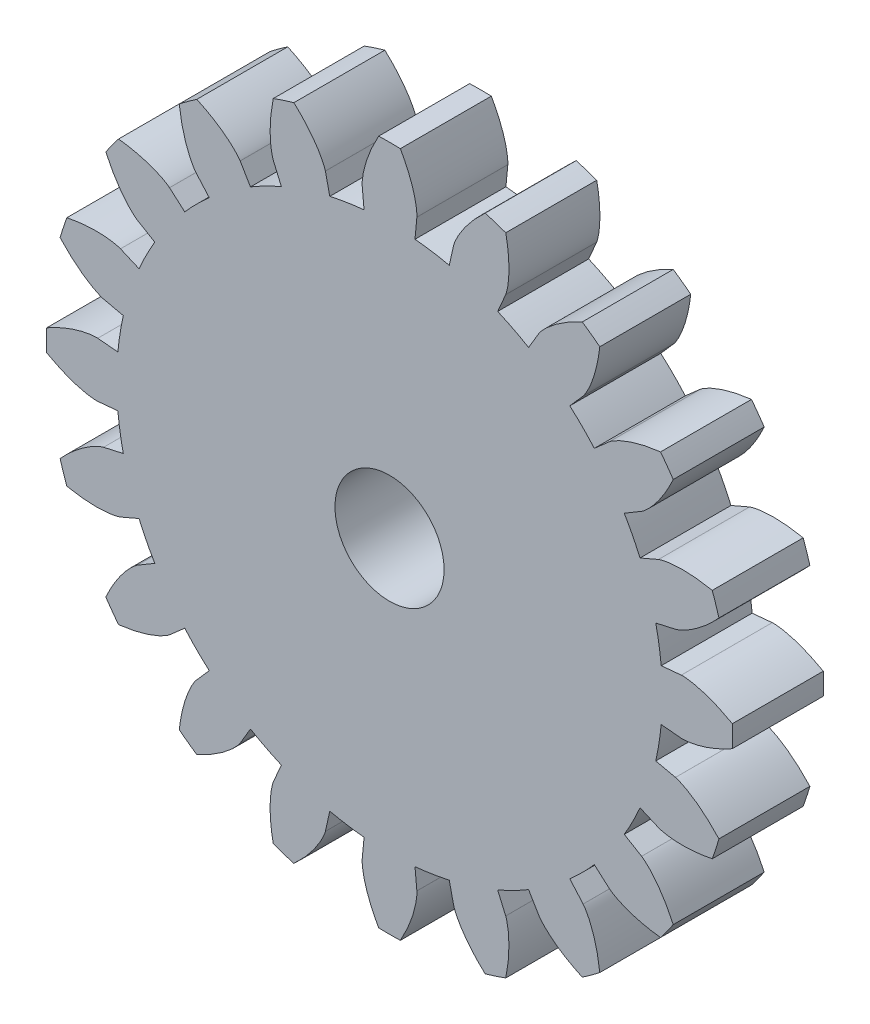
SolidWorks part; units mm, degrees
ref_plane "Plan de face" through (0, 0, 0) normal (0, 0, 1) x (1, 0, 0)
ref_plane "Plan de dessus" through (0, 0, 0) normal (0, 1, 0) x (1, 0, 0)
ref_plane "Plan de droite" through (0, 0, 0) normal (1, 0, 0) x (0, 0, -1)
sketch "Esquisse1" plane through (0, 0, 0) normal (0, 0, 1) x (1, 0, 0)
  line L0 (15.0618, -1.9866) -> (16.166, -2.0901)
  line L1 (16.166, -2.0901) -> (16.1672, -2.0902)
  line L2 (16.1672, 0.9162) -> (16.166, 0.9161)
  line L3 (16.166, 0.9161) -> (15.0618, 0.8126)
  line L4 (14.7634, 2.6969) -> (15.8455, 2.9397)
  line L5 (15.8455, 2.9397) -> (15.8467, 2.94)
  line L6 (14.9177, 5.7993) -> (14.9165, 5.7988)
  line L7 (14.9165, 5.7988) -> (13.8984, 5.3592)
  line L8 (13.0323, 7.059) -> (13.9864, 7.6243)
  line L9 (13.9864, 7.6243) -> (13.9875, 7.625)
  line L10 (12.2203, 10.0572) -> (12.2194, 10.0564)
  line L11 (12.2194, 10.0564) -> (11.3869, 9.3237)
  line L12 (10.0379, 10.6727) -> (10.7706, 11.5051)
  line L13 (10.7706, 11.5051) -> (10.7715, 11.5061)
  line L14 (8.3392, 13.2732) -> (8.3386, 13.2721)
  line L15 (8.3386, 13.2721) -> (7.7733, 12.318)
  line L16 (6.0734, 13.1841) -> (6.5131, 14.2023)
  line L17 (6.5131, 14.2023) -> (6.5135, 14.2034)
  line L18 (3.6543, 15.1325) -> (3.654, 15.1313)
  line L19 (3.654, 15.1313) -> (3.4112, 14.0491)
  line L20 (1.5269, 14.3476) -> (1.6304, 15.4518)
  line L21 (1.6304, 15.4518) -> (1.6305, 15.453)
  line L22 (-1.3759, 15.453) -> (-1.3758, 15.4518)
  line L23 (-1.3758, 15.4518) -> (-1.2724, 14.3476)
  line L24 (-3.1566, 14.0491) -> (-3.3994, 15.1313)
  line L25 (-3.3994, 15.1313) -> (-3.3997, 15.1325)
  line L26 (-6.259, 14.2034) -> (-6.2585, 14.2023)
  line L27 (-6.2585, 14.2023) -> (-5.8189, 13.1841)
  line L28 (-7.5187, 12.318) -> (-8.084, 13.2721)
  line L29 (-8.084, 13.2721) -> (-8.0847, 13.2732)
  line L30 (-10.5169, 11.5061) -> (-10.5161, 11.5051)
  line L31 (-10.5161, 11.5051) -> (-9.7834, 10.6727)
  line L32 (-11.1324, 9.3237) -> (-11.9648, 10.0564)
  line L33 (-11.9648, 10.0564) -> (-11.9658, 10.0572)
  line L34 (-13.7329, 7.625) -> (-13.7318, 7.6243)
  line L35 (-13.7318, 7.6243) -> (-12.7777, 7.059)
  line L36 (-13.6438, 5.3592) -> (-14.662, 5.7988)
  line L37 (-14.662, 5.7988) -> (-14.6631, 5.7993)
  line L38 (-15.5922, 2.94) -> (-15.591, 2.9397)
  line L39 (-15.591, 2.9397) -> (-14.5088, 2.6969)
  line L40 (-14.8073, 0.8126) -> (-15.9115, 0.9161)
  line L41 (-15.9115, 0.9161) -> (-15.9127, 0.9162)
  line L42 (-15.9127, -2.0902) -> (-15.9115, -2.0901)
  line L43 (-15.9115, -2.0901) -> (-14.8073, -1.9866)
  line L44 (-14.5088, -3.8709) -> (-15.591, -4.1137)
  line L45 (-15.591, -4.1137) -> (-15.5922, -4.114)
  line L46 (-14.6631, -6.9732) -> (-14.662, -6.9728)
  line L47 (-14.662, -6.9728) -> (-13.6438, -6.5331)
  line L48 (-12.7777, -8.233) -> (-13.7318, -8.7983)
  line L49 (-13.7318, -8.7983) -> (-13.7329, -8.7989)
  line L50 (-11.9658, -11.2312) -> (-11.9648, -11.2303)
  line L51 (-11.9648, -11.2303) -> (-11.1324, -10.4976)
  line L52 (-9.7834, -11.8466) -> (-10.5161, -12.6791)
  line L53 (-10.5161, -12.6791) -> (-10.5169, -12.68)
  line L54 (-8.0847, -14.4472) -> (-8.084, -14.4461)
  line L55 (-8.084, -14.4461) -> (-7.5187, -13.492)
  line L56 (-5.8189, -14.3581) -> (-6.2585, -15.3762)
  line L57 (-6.2585, -15.3762) -> (-6.259, -15.3774)
  line L58 (-3.3997, -16.3064) -> (-3.3994, -16.3052)
  line L59 (-3.3994, -16.3052) -> (-3.1566, -15.2231)
  line L60 (-1.2724, -15.5215) -> (-1.3758, -16.6257)
  line L61 (-1.3758, -16.6257) -> (-1.3759, -16.6269)
  line L62 (1.6305, -16.6269) -> (1.6304, -16.6257)
  line L63 (1.6304, -16.6257) -> (1.5269, -15.5215)
  line L64 (3.4112, -15.2231) -> (3.654, -16.3052)
  line L65 (3.654, -16.3052) -> (3.6543, -16.3064)
  line L66 (6.5135, -15.3774) -> (6.5131, -15.3762)
  line L67 (6.5131, -15.3762) -> (6.0734, -14.3581)
  line L68 (7.7733, -13.492) -> (8.3386, -14.4461)
  line L69 (8.3386, -14.4461) -> (8.3392, -14.4472)
  line L70 (10.7715, -12.68) -> (10.7706, -12.6791)
  line L71 (10.7706, -12.6791) -> (10.0379, -11.8466)
  line L72 (11.3869, -10.4976) -> (12.2194, -11.2303)
  line L73 (12.2194, -11.2303) -> (12.2203, -11.2312)
  line L74 (13.9875, -8.7989) -> (13.9864, -8.7983)
  line L75 (13.9864, -8.7983) -> (13.0323, -8.233)
  line L76 (13.8984, -6.5331) -> (14.9165, -6.9728)
  line L77 (14.9165, -6.9728) -> (14.9177, -6.9732)
  line L78 (15.8467, -4.114) -> (15.8455, -4.1137)
  line L79 (15.8455, -4.1137) -> (14.7634, -3.8709)
  arc A0 (14.7634, -3.8709) -> (15.0618, -1.9866) centre (0.1273, -0.587) ccw
  arc A1 (18.975, -1.1825) -> (18.975, 0.0085) centre (0.1273, -0.587) ccw
  arc A2 (15.0618, 0.8126) -> (14.7634, 2.6969) centre (0.1273, -0.587) ccw
  arc A3 (18.2366, 4.6709) -> (17.8685, 5.8037) centre (0.1273, -0.587) ccw
  arc A4 (13.8984, 5.3592) -> (13.0323, 7.059) centre (0.1273, -0.587) ccw
  arc A5 (15.7254, 10.0097) -> (15.0254, 10.9732) centre (0.1273, -0.587) ccw
  arc A6 (11.3869, 9.3237) -> (10.0379, 10.6727) centre (0.1273, -0.587) ccw
  arc A7 (11.6875, 14.3111) -> (10.7239, 15.0112) centre (0.1273, -0.587) ccw
  arc A8 (7.7733, 12.318) -> (6.0734, 13.1841) centre (0.1273, -0.587) ccw
  arc A9 (6.5179, 17.1543) -> (5.3852, 17.5223) centre (0.1273, -0.587) ccw
  arc A10 (3.4112, 14.0491) -> (1.5269, 14.3476) centre (0.1273, -0.587) ccw
  arc A11 (0.7228, 18.2608) -> (-0.4682, 18.2608) centre (0.1273, -0.587) ccw
  arc A12 (-1.2724, 14.3476) -> (-3.1566, 14.0491) centre (0.1273, -0.587) ccw
  arc A13 (-5.1306, 17.5223) -> (-6.2634, 17.1543) centre (0.1273, -0.587) ccw
  arc A14 (-5.8189, 13.1841) -> (-7.5187, 12.318) centre (0.1273, -0.587) ccw
  arc A15 (-10.4694, 15.0112) -> (-11.4329, 14.3111) centre (0.1273, -0.587) ccw
  arc A16 (-9.7834, 10.6727) -> (-11.1324, 9.3237) centre (0.1273, -0.587) ccw
  arc A17 (-14.7708, 10.9732) -> (-15.4709, 10.0097) centre (0.1273, -0.587) ccw
  arc A18 (-12.7777, 7.059) -> (-13.6438, 5.3592) centre (0.1273, -0.587) ccw
  arc A19 (-17.614, 5.8037) -> (-17.982, 4.6709) centre (0.1273, -0.587) ccw
  arc A20 (-14.5088, 2.6969) -> (-14.8073, 0.8126) centre (0.1273, -0.587) ccw
  arc A21 (-18.7205, 0.0085) -> (-18.7205, -1.1825) centre (0.1273, -0.587) ccw
  arc A22 (-14.8073, -1.9866) -> (-14.5088, -3.8709) centre (0.1273, -0.587) ccw
  arc A23 (-17.982, -5.8449) -> (-17.614, -6.9776) centre (0.1273, -0.587) ccw
  arc A24 (-13.6438, -6.5331) -> (-12.7777, -8.233) centre (0.1273, -0.587) ccw
  arc A25 (-15.4709, -11.1836) -> (-14.7708, -12.1472) centre (0.1273, -0.587) ccw
  arc A26 (-11.1324, -10.4976) -> (-9.7834, -11.8466) centre (0.1273, -0.587) ccw
  arc A27 (-11.4329, -15.4851) -> (-10.4694, -16.1851) centre (0.1273, -0.587) ccw
  arc A28 (-7.5187, -13.492) -> (-5.8189, -14.3581) centre (0.1273, -0.587) ccw
  arc A29 (-6.2634, -18.3282) -> (-5.1306, -18.6963) centre (0.1273, -0.587) ccw
  arc A30 (-3.1566, -15.2231) -> (-1.2724, -15.5215) centre (0.1273, -0.587) ccw
  arc A31 (-0.4682, -19.4347) -> (0.7228, -19.4347) centre (0.1273, -0.587) ccw
  arc A32 (1.5269, -15.5215) -> (3.4112, -15.2231) centre (0.1273, -0.587) ccw
  arc A33 (5.3852, -18.6963) -> (6.5179, -18.3282) centre (0.1273, -0.587) ccw
  arc A34 (6.0734, -14.3581) -> (7.7733, -13.492) centre (0.1273, -0.587) ccw
  arc A35 (10.7239, -16.1851) -> (11.6875, -15.4851) centre (0.1273, -0.587) ccw
  arc A36 (10.0379, -11.8466) -> (11.3869, -10.4976) centre (0.1273, -0.587) ccw
  arc A37 (15.0254, -12.1472) -> (15.7254, -11.1836) centre (0.1273, -0.587) ccw
  arc A38 (13.0323, -8.233) -> (13.8984, -6.5331) centre (0.1273, -0.587) ccw
  arc A39 (17.8685, -6.9776) -> (18.2366, -5.8449) centre (0.1273, -0.587) ccw
  spline S0 degree 5 poles (16.1672, -2.0902) (16.168, -2.0902) (16.1695, -2.0904) (16.1722, -2.0906) (16.1781, -2.0909) (16.1878, -2.0914) (16.1996, -2.0918) (16.2161, -2.0922) (16.2383, -2.0924) (16.2646, -2.0921) (16.2978, -2.0913) (16.3386, -2.0896) (16.388, -2.0865) (16.4465, -2.0817) (16.515, -2.0746) (16.596, -2.0644) (16.6885, -2.0505) (16.7929, -2.0322) (16.9096, -2.0087) (17.0392, -1.9792) (17.1818, -1.9428) (17.3378, -1.8984) (17.5073, -1.8452) (17.6906, -1.7819) (17.8876, -1.7074) (18.1071, -1.6173) (18.3138, -1.5248) (18.5026, -1.434) (18.6721, -1.3477) (18.8059, -1.2764) (18.8809, -1.2353) (18.9342, -1.2055) (18.9656, -1.1878) (18.975, -1.1825) knots 0 0 0 0 0 0 0.016667 0.025 0.033333 0.054167 0.066667 0.083333 0.104167 0.125 0.15 0.175 0.204167 0.2375 0.270833 0.308333 0.35 0.391667 0.4375 0.483333 0.533333 0.5875 0.641667 0.7 0.758333 0.820833 0.9 0.929167 0.958333 0.9875 1 1 1 1 1 1 weights 1 1 1 1 1 1 1 1 1 1 1 1 1 1 1 1 1 1 1 1 1 1 1 1 1 1 1 1 1 1 1 1 1 1
  spline S1 degree 5 poles (18.975, 0.0085) (18.9153, 0.0423) (18.837, 0.0857) (18.7341, 0.1412) (18.5949, 0.2136) (18.4234, 0.298) (18.278, 0.3664) (18.1136, 0.4396) (17.9373, 0.5133) (17.7616, 0.5816) (17.5816, 0.6462) (17.3961, 0.707) (17.2119, 0.7612) (17.0307, 0.8081) (16.8333, 0.8519) (16.6491, 0.8844) (16.4939, 0.9045) (16.3642, 0.9152) (16.2755, 0.9184) (16.2285, 0.9185) (16.2015, 0.918) (16.1853, 0.9173) (16.1771, 0.9169) (16.1721, 0.9166) (16.1692, 0.9164) (16.1678, 0.9163) (16.1672, 0.9162) knots -1 -1 -1 -1 -1 -1 -0.920833 -0.895833 -0.8625 -0.8125 -0.766667 -0.720833 -0.666667 -0.6125 -0.558333 -0.5 -0.4375 -0.375 -0.3125 -0.2125 -0.15 -0.108333 -0.058333 -0.045833 -0.0375 -0.025 -0.0125 0 0 0 0 0 0 weights 1 1 1 1 1 1 1 1 1 1 1 1 1 1 1 1 1 1 1 1 1 1 1 1 1 1 1
  spline S2 degree 5 poles (15.8467, 2.94) (15.8475, 2.9402) (15.8489, 2.9405) (15.8516, 2.9412) (15.8573, 2.9427) (15.8666, 2.9452) (15.878, 2.9484) (15.8938, 2.9532) (15.915, 2.9599) (15.9399, 2.9682) (15.9712, 2.9793) (16.0095, 2.9936) (16.0555, 3.0117) (16.1097, 3.0344) (16.1727, 3.0623) (16.2466, 3.0971) (16.3302, 3.1388) (16.4238, 3.1885) (16.5276, 3.2469) (16.6417, 3.315) (16.766, 3.3937) (16.9007, 3.4841) (17.0455, 3.5871) (17.2002, 3.704) (17.3646, 3.8356) (17.5455, 3.9893) (17.7135, 4.1411) (17.865, 4.2857) (17.9996, 4.4202) (18.1047, 4.5294) (18.1634, 4.5916) (18.2049, 4.6364) (18.2292, 4.6629) (18.2366, 4.6709) knots 0 0 0 0 0 0 0.016667 0.025 0.033333 0.054167 0.066667 0.083333 0.104167 0.125 0.15 0.175 0.204167 0.2375 0.270833 0.308333 0.35 0.391667 0.4375 0.483333 0.533333 0.5875 0.641667 0.7 0.758333 0.820833 0.9 0.929167 0.958333 0.9875 1 1 1 1 1 1 weights 1 1 1 1 1 1 1 1 1 1 1 1 1 1 1 1 1 1 1 1 1 1 1 1 1 1 1 1 1 1 1 1 1 1
  spline S3 degree 5 poles (17.8685, 5.8037) (17.8013, 5.8174) (17.7134, 5.8344) (17.5984, 5.8554) (17.4436, 5.8812) (17.2545, 5.9085) (17.0951, 5.9286) (16.9161, 5.9475) (16.7256, 5.963) (16.5374, 5.9737) (16.3463, 5.9796) (16.151, 5.98) (15.9591, 5.9746) (15.7723, 5.9632) (15.571, 5.9439) (15.3858, 5.9179) (15.2319, 5.889) (15.1053, 5.8592) (15.02, 5.8348) (14.9752, 5.8204) (14.9497, 5.8115) (14.9345, 5.8059) (14.9269, 5.803) (14.9222, 5.8011) (14.9195, 5.8001) (14.9182, 5.7995) (14.9177, 5.7993) knots -1 -1 -1 -1 -1 -1 -0.920833 -0.895833 -0.8625 -0.8125 -0.766667 -0.720833 -0.666667 -0.6125 -0.558333 -0.5 -0.4375 -0.375 -0.3125 -0.2125 -0.15 -0.108333 -0.058333 -0.045833 -0.0375 -0.025 -0.0125 0 0 0 0 0 0 weights 1 1 1 1 1 1 1 1 1 1 1 1 1 1 1 1 1 1 1 1 1 1 1 1 1 1 1
  spline S4 degree 5 poles (13.9875, 7.625) (13.9881, 7.6254) (13.9894, 7.6261) (13.9917, 7.6276) (13.9967, 7.6307) (14.0048, 7.6361) (14.0146, 7.6426) (14.0281, 7.652) (14.0462, 7.665) (14.0673, 7.6806) (14.0937, 7.7008) (14.1257, 7.7262) (14.1639, 7.7577) (14.2084, 7.796) (14.2597, 7.842) (14.3192, 7.8979) (14.3858, 7.9635) (14.4595, 8.0396) (14.5402, 8.1272) (14.6276, 8.2272) (14.7216, 8.3405) (14.8217, 8.4681) (14.9276, 8.6109) (15.0386, 8.7698) (15.1543, 8.9458) (15.2789, 9.1478) (15.3917, 9.3441) (15.4911, 9.5285) (15.5775, 9.698) (15.6438, 9.8343) (15.6803, 9.9116) (15.706, 9.967) (15.721, 9.9998) (15.7254, 10.0097) knots 0 0 0 0 0 0 0.016667 0.025 0.033333 0.054167 0.066667 0.083333 0.104167 0.125 0.15 0.175 0.204167 0.2375 0.270833 0.308333 0.35 0.391667 0.4375 0.483333 0.533333 0.5875 0.641667 0.7 0.758333 0.820833 0.9 0.929167 0.958333 0.9875 1 1 1 1 1 1 weights 1 1 1 1 1 1 1 1 1 1 1 1 1 1 1 1 1 1 1 1 1 1 1 1 1 1 1 1 1 1 1 1 1 1
  spline S5 degree 5 poles (15.0254, 10.9732) (14.9572, 10.9655) (14.8684, 10.9546) (14.7525, 10.939) (14.5973, 10.9157) (14.409, 10.8832) (14.2512, 10.8531) (14.0751, 10.8157) (13.8892, 10.7716) (13.7069, 10.7236) (13.5233, 10.6701) (13.3374, 10.6102) (13.1566, 10.5458) (12.9824, 10.4772) (12.797, 10.3966) (12.6289, 10.3147) (12.4915, 10.2397) (12.3803, 10.1722) (12.3067, 10.1226) (12.2685, 10.0951) (12.247, 10.0787) (12.2343, 10.0687) (12.2279, 10.0636) (12.2241, 10.0604) (12.2218, 10.0585) (12.2208, 10.0576) (12.2203, 10.0572) knots -1 -1 -1 -1 -1 -1 -0.920833 -0.895833 -0.8625 -0.8125 -0.766667 -0.720833 -0.666667 -0.6125 -0.558333 -0.5 -0.4375 -0.375 -0.3125 -0.2125 -0.15 -0.108333 -0.058333 -0.045833 -0.0375 -0.025 -0.0125 0 0 0 0 0 0 weights 1 1 1 1 1 1 1 1 1 1 1 1 1 1 1 1 1 1 1 1 1 1 1 1 1 1 1
  spline S6 degree 5 poles (10.7715, 11.5061) (10.772, 11.5067) (10.7729, 11.5078) (10.7747, 11.5099) (10.7784, 11.5144) (10.7845, 11.522) (10.7918, 11.5313) (10.8018, 11.5444) (10.815, 11.5623) (10.8302, 11.5837) (10.8491, 11.611) (10.8717, 11.6451) (10.8982, 11.6868) (10.9288, 11.737) (10.9633, 11.7966) (11.0026, 11.8681) (11.0457, 11.9511) (11.0923, 12.0463) (11.1419, 12.1546) (11.1942, 12.2767) (11.2485, 12.4135) (11.3043, 12.5657) (11.3609, 12.7342) (11.4174, 12.9197) (11.473, 13.1229) (11.5291, 13.3534) (11.5757, 13.575) (11.6133, 13.7811) (11.6431, 13.969) (11.664, 14.1191) (11.6749, 14.204) (11.6821, 14.2645) (11.6863, 14.3004) (11.6875, 14.3111) knots 0 0 0 0 0 0 0.016667 0.025 0.033333 0.054167 0.066667 0.083333 0.104167 0.125 0.15 0.175 0.204167 0.2375 0.270833 0.308333 0.35 0.391667 0.4375 0.483333 0.533333 0.5875 0.641667 0.7 0.758333 0.820833 0.9 0.929167 0.958333 0.9875 1 1 1 1 1 1 weights 1 1 1 1 1 1 1 1 1 1 1 1 1 1 1 1 1 1 1 1 1 1 1 1 1 1 1 1 1 1 1 1 1 1
  spline S7 degree 5 poles (10.7239, 15.0112) (10.6615, 14.9828) (10.5804, 14.9449) (10.475, 14.8943) (10.3346, 14.8242) (10.1655, 14.7351) (10.0247, 14.6577) (9.8688, 14.5677) (9.7056, 14.4683) (9.5471, 14.3663) (9.389, 14.2588) (9.2308, 14.1443) (9.0787, 14.0272) (8.9342, 13.9082) (8.7828, 13.7742) (8.6482, 13.6443) (8.5407, 13.5305) (8.4558, 13.432) (8.4011, 13.3621) (8.3733, 13.3241) (8.3579, 13.3019) (8.3489, 13.2885) (8.3445, 13.2816) (8.3418, 13.2774) (8.3402, 13.2749) (8.3395, 13.2737) (8.3392, 13.2732) knots -1 -1 -1 -1 -1 -1 -0.920833 -0.895833 -0.8625 -0.8125 -0.766667 -0.720833 -0.666667 -0.6125 -0.558333 -0.5 -0.4375 -0.375 -0.3125 -0.2125 -0.15 -0.108333 -0.058333 -0.045833 -0.0375 -0.025 -0.0125 0 0 0 0 0 0 weights 1 1 1 1 1 1 1 1 1 1 1 1 1 1 1 1 1 1 1 1 1 1 1 1 1 1 1
  spline S8 degree 5 poles (6.5135, 14.2034) (6.5138, 14.2041) (6.5144, 14.2055) (6.5154, 14.208) (6.5176, 14.2135) (6.521, 14.2226) (6.5251, 14.2337) (6.5305, 14.2492) (6.5376, 14.2704) (6.5455, 14.2954) (6.5549, 14.3272) (6.5659, 14.3666) (6.5783, 14.4145) (6.5918, 14.4717) (6.6062, 14.539) (6.6215, 14.6192) (6.6369, 14.7115) (6.6517, 14.8163) (6.6655, 14.9347) (6.6774, 15.067) (6.6869, 15.2138) (6.6929, 15.3759) (6.6946, 15.5536) (6.691, 15.7475) (6.6812, 15.9579) (6.6632, 16.1945) (6.6391, 16.4196) (6.6112, 16.6272) (6.5814, 16.8152) (6.5549, 16.9644) (6.539, 17.0484) (6.5272, 17.1083) (6.5201, 17.1437) (6.5179, 17.1543) knots 0 0 0 0 0 0 0.016667 0.025 0.033333 0.054167 0.066667 0.083333 0.104167 0.125 0.15 0.175 0.204167 0.2375 0.270833 0.308333 0.35 0.391667 0.4375 0.483333 0.533333 0.5875 0.641667 0.7 0.758333 0.820833 0.9 0.929167 0.958333 0.9875 1 1 1 1 1 1 weights 1 1 1 1 1 1 1 1 1 1 1 1 1 1 1 1 1 1 1 1 1 1 1 1 1 1 1 1 1 1 1 1 1 1
  spline S9 degree 5 poles (5.3852, 17.5223) (5.3346, 17.476) (5.2691, 17.4149) (5.1846, 17.3342) (5.0727, 17.2241) (4.9395, 17.0872) (4.8295, 16.97) (4.709, 16.8363) (4.5845, 16.6914) (4.4652, 16.5454) (4.3481, 16.3942) (4.233, 16.2365) (4.1246, 16.078) (4.0239, 15.9202) (3.9213, 15.746) (3.8334, 15.5809) (3.7664, 15.4395) (3.7161, 15.3195) (3.6857, 15.2361) (3.671, 15.1914) (3.6632, 15.1656) (3.6588, 15.15) (3.6567, 15.1421) (3.6554, 15.1372) (3.6547, 15.1344) (3.6544, 15.133) (3.6543, 15.1325) knots -1 -1 -1 -1 -1 -1 -0.920833 -0.895833 -0.8625 -0.8125 -0.766667 -0.720833 -0.666667 -0.6125 -0.558333 -0.5 -0.4375 -0.375 -0.3125 -0.2125 -0.15 -0.108333 -0.058333 -0.045833 -0.0375 -0.025 -0.0125 0 0 0 0 0 0 weights 1 1 1 1 1 1 1 1 1 1 1 1 1 1 1 1 1 1 1 1 1 1 1 1 1 1 1
  spline S10 degree 5 poles (1.6305, 15.453) (1.6305, 15.4538) (1.6307, 15.4553) (1.6309, 15.458) (1.6312, 15.4639) (1.6317, 15.4736) (1.6321, 15.4853) (1.6325, 15.5018) (1.6327, 15.5241) (1.6324, 15.5503) (1.6316, 15.5835) (1.6299, 15.6244) (1.6268, 15.6737) (1.622, 15.7323) (1.6149, 15.8008) (1.6047, 15.8818) (1.5908, 15.9743) (1.5725, 16.0786) (1.549, 16.1954) (1.5195, 16.3249) (1.4831, 16.4675) (1.4387, 16.6235) (1.3855, 16.7931) (1.3222, 16.9763) (1.2477, 17.1734) (1.1576, 17.3929) (1.0651, 17.5995) (0.9743, 17.7883) (0.888, 17.9579) (0.8167, 18.0916) (0.7756, 18.1666) (0.7458, 18.2199) (0.7281, 18.2513) (0.7228, 18.2608) knots 0 0 0 0 0 0 0.016667 0.025 0.033333 0.054167 0.066667 0.083333 0.104167 0.125 0.15 0.175 0.204167 0.2375 0.270833 0.308333 0.35 0.391667 0.4375 0.483333 0.533333 0.5875 0.641667 0.7 0.758333 0.820833 0.9 0.929167 0.958333 0.9875 1 1 1 1 1 1 weights 1 1 1 1 1 1 1 1 1 1 1 1 1 1 1 1 1 1 1 1 1 1 1 1 1 1 1 1 1 1 1 1 1 1
  spline S11 degree 5 poles (-0.4682, 18.2608) (-0.502, 18.2011) (-0.5454, 18.1228) (-0.6009, 18.0199) (-0.6733, 17.8806) (-0.7577, 17.7092) (-0.8261, 17.5638) (-0.8993, 17.3994) (-0.973, 17.223) (-1.0413, 17.0473) (-1.1059, 16.8674) (-1.1667, 16.6818) (-1.2209, 16.4976) (-1.2678, 16.3164) (-1.3116, 16.119) (-1.3441, 15.9349) (-1.3642, 15.7796) (-1.3749, 15.65) (-1.3781, 15.5613) (-1.3782, 15.5142) (-1.3777, 15.4872) (-1.377, 15.4711) (-1.3766, 15.4629) (-1.3763, 15.4579) (-1.3761, 15.455) (-1.376, 15.4536) (-1.3759, 15.453) knots -1 -1 -1 -1 -1 -1 -0.920833 -0.895833 -0.8625 -0.8125 -0.766667 -0.720833 -0.666667 -0.6125 -0.558333 -0.5 -0.4375 -0.375 -0.3125 -0.2125 -0.15 -0.108333 -0.058333 -0.045833 -0.0375 -0.025 -0.0125 0 0 0 0 0 0 weights 1 1 1 1 1 1 1 1 1 1 1 1 1 1 1 1 1 1 1 1 1 1 1 1 1 1 1
  spline S12 degree 5 poles (-3.3997, 15.1325) (-3.3999, 15.1332) (-3.4002, 15.1347) (-3.4009, 15.1373) (-3.4024, 15.143) (-3.4049, 15.1524) (-3.4081, 15.1637) (-3.4129, 15.1795) (-3.4196, 15.2008) (-3.4279, 15.2256) (-3.439, 15.2569) (-3.4533, 15.2953) (-3.4714, 15.3412) (-3.4941, 15.3955) (-3.522, 15.4584) (-3.5568, 15.5323) (-3.5985, 15.616) (-3.6482, 15.7095) (-3.7066, 15.8134) (-3.7747, 15.9274) (-3.8534, 16.0518) (-3.9438, 16.1864) (-4.0468, 16.3312) (-4.1637, 16.486) (-4.2953, 16.6504) (-4.449, 16.8313) (-4.6008, 16.9992) (-4.7454, 17.1507) (-4.8799, 17.2853) (-4.9891, 17.3905) (-5.0513, 17.4491) (-5.0961, 17.4906) (-5.1226, 17.515) (-5.1306, 17.5223) knots 0 0 0 0 0 0 0.016667 0.025 0.033333 0.054167 0.066667 0.083333 0.104167 0.125 0.15 0.175 0.204167 0.2375 0.270833 0.308333 0.35 0.391667 0.4375 0.483333 0.533333 0.5875 0.641667 0.7 0.758333 0.820833 0.9 0.929167 0.958333 0.9875 1 1 1 1 1 1 weights 1 1 1 1 1 1 1 1 1 1 1 1 1 1 1 1 1 1 1 1 1 1 1 1 1 1 1 1 1 1 1 1 1 1
  spline S13 degree 5 poles (-6.2634, 17.1543) (-6.2771, 17.087) (-6.2941, 16.9992) (-6.3151, 16.8842) (-6.3409, 16.7294) (-6.3682, 16.5403) (-6.3883, 16.3808) (-6.4072, 16.2018) (-6.4227, 16.0114) (-6.4334, 15.8231) (-6.4393, 15.632) (-6.4397, 15.4368) (-6.4343, 15.2448) (-6.4229, 15.058) (-6.4036, 14.8567) (-6.3776, 14.6716) (-6.3487, 14.5177) (-6.3189, 14.3911) (-6.2945, 14.3057) (-6.2801, 14.261) (-6.2712, 14.2355) (-6.2656, 14.2203) (-6.2627, 14.2126) (-6.2608, 14.208) (-6.2598, 14.2053) (-6.2592, 14.204) (-6.259, 14.2034) knots -1 -1 -1 -1 -1 -1 -0.920833 -0.895833 -0.8625 -0.8125 -0.766667 -0.720833 -0.666667 -0.6125 -0.558333 -0.5 -0.4375 -0.375 -0.3125 -0.2125 -0.15 -0.108333 -0.058333 -0.045833 -0.0375 -0.025 -0.0125 0 0 0 0 0 0 weights 1 1 1 1 1 1 1 1 1 1 1 1 1 1 1 1 1 1 1 1 1 1 1 1 1 1 1
  spline S14 degree 5 poles (-8.0847, 13.2732) (-8.0851, 13.2739) (-8.0858, 13.2751) (-8.0873, 13.2774) (-8.0904, 13.2824) (-8.0958, 13.2905) (-8.1023, 13.3003) (-8.1117, 13.3139) (-8.1247, 13.332) (-8.1403, 13.3531) (-8.1605, 13.3795) (-8.1859, 13.4115) (-8.2174, 13.4496) (-8.2557, 13.4942) (-8.3017, 13.5454) (-8.3576, 13.6049) (-8.4232, 13.6716) (-8.4993, 13.7453) (-8.5869, 13.8259) (-8.6869, 13.9134) (-8.8002, 14.0073) (-8.9278, 14.1074) (-9.0706, 14.2133) (-9.2295, 14.3244) (-9.4055, 14.4401) (-9.6075, 14.5646) (-9.8038, 14.6774) (-9.9882, 14.7768) (-10.1577, 14.8633) (-10.294, 14.9296) (-10.3713, 14.9661) (-10.4267, 14.9917) (-10.4595, 15.0067) (-10.4694, 15.0112) knots 0 0 0 0 0 0 0.016667 0.025 0.033333 0.054167 0.066667 0.083333 0.104167 0.125 0.15 0.175 0.204167 0.2375 0.270833 0.308333 0.35 0.391667 0.4375 0.483333 0.533333 0.5875 0.641667 0.7 0.758333 0.820833 0.9 0.929167 0.958333 0.9875 1 1 1 1 1 1 weights 1 1 1 1 1 1 1 1 1 1 1 1 1 1 1 1 1 1 1 1 1 1 1 1 1 1 1 1 1 1 1 1 1 1
  spline S15 degree 5 poles (-11.4329, 14.3111) (-11.4252, 14.243) (-11.4143, 14.1541) (-11.3987, 14.0383) (-11.3754, 13.8831) (-11.3429, 13.6948) (-11.3128, 13.5369) (-11.2754, 13.3608) (-11.2313, 13.1749) (-11.1833, 12.9926) (-11.1298, 12.809) (-11.0699, 12.6232) (-11.0055, 12.4423) (-10.9369, 12.2682) (-10.8563, 12.0827) (-10.7744, 11.9146) (-10.6994, 11.7772) (-10.6319, 11.666) (-10.5823, 11.5924) (-10.5548, 11.5543) (-10.5384, 11.5328) (-10.5284, 11.52) (-10.5233, 11.5137) (-10.5201, 11.5098) (-10.5182, 11.5076) (-10.5173, 11.5065) (-10.5169, 11.5061) knots -1 -1 -1 -1 -1 -1 -0.920833 -0.895833 -0.8625 -0.8125 -0.766667 -0.720833 -0.666667 -0.6125 -0.558333 -0.5 -0.4375 -0.375 -0.3125 -0.2125 -0.15 -0.108333 -0.058333 -0.045833 -0.0375 -0.025 -0.0125 0 0 0 0 0 0 weights 1 1 1 1 1 1 1 1 1 1 1 1 1 1 1 1 1 1 1 1 1 1 1 1 1 1 1
  spline S16 degree 5 poles (-11.9658, 10.0572) (-11.9664, 10.0577) (-11.9675, 10.0587) (-11.9696, 10.0604) (-11.9741, 10.0642) (-11.9817, 10.0703) (-11.991, 10.0775) (-12.0041, 10.0875) (-12.022, 10.1008) (-12.0434, 10.116) (-12.0707, 10.1348) (-12.1048, 10.1574) (-12.1465, 10.184) (-12.1967, 10.2145) (-12.2563, 10.249) (-12.3278, 10.2884) (-12.4108, 10.3315) (-12.506, 10.378) (-12.6143, 10.4277) (-12.7364, 10.4799) (-12.8732, 10.5343) (-13.0254, 10.5901) (-13.1939, 10.6467) (-13.3794, 10.7032) (-13.5826, 10.7588) (-13.8131, 10.8148) (-14.0347, 10.8615) (-14.2408, 10.899) (-14.4287, 10.9289) (-14.5788, 10.9498) (-14.6637, 10.9606) (-14.7242, 10.9679) (-14.7601, 10.972) (-14.7708, 10.9732) knots 0 0 0 0 0 0 0.016667 0.025 0.033333 0.054167 0.066667 0.083333 0.104167 0.125 0.15 0.175 0.204167 0.2375 0.270833 0.308333 0.35 0.391667 0.4375 0.483333 0.533333 0.5875 0.641667 0.7 0.758333 0.820833 0.9 0.929167 0.958333 0.9875 1 1 1 1 1 1 weights 1 1 1 1 1 1 1 1 1 1 1 1 1 1 1 1 1 1 1 1 1 1 1 1 1 1 1 1 1 1 1 1 1 1
  spline S17 degree 5 poles (-15.4709, 10.0097) (-15.4425, 9.9472) (-15.4046, 9.8661) (-15.354, 9.7608) (-15.2839, 9.6204) (-15.1948, 9.4513) (-15.1174, 9.3105) (-15.0274, 9.1546) (-14.928, 8.9914) (-14.8261, 8.8328) (-14.7185, 8.6748) (-14.604, 8.5165) (-14.4869, 8.3644) (-14.3679, 8.22) (-14.2339, 8.0685) (-14.104, 7.934) (-13.9902, 7.8264) (-13.8917, 7.7416) (-13.8218, 7.6869) (-13.7838, 7.6591) (-13.7616, 7.6437) (-13.7482, 7.6347) (-13.7413, 7.6302) (-13.7371, 7.6275) (-13.7346, 7.626) (-13.7334, 7.6253) (-13.7329, 7.625) knots -1 -1 -1 -1 -1 -1 -0.920833 -0.895833 -0.8625 -0.8125 -0.766667 -0.720833 -0.666667 -0.6125 -0.558333 -0.5 -0.4375 -0.375 -0.3125 -0.2125 -0.15 -0.108333 -0.058333 -0.045833 -0.0375 -0.025 -0.0125 0 0 0 0 0 0 weights 1 1 1 1 1 1 1 1 1 1 1 1 1 1 1 1 1 1 1 1 1 1 1 1 1 1 1
  spline S18 degree 5 poles (-14.6631, 5.7993) (-14.6638, 5.7996) (-14.6652, 5.8002) (-14.6677, 5.8012) (-14.6732, 5.8033) (-14.6823, 5.8068) (-14.6934, 5.8108) (-14.7089, 5.8163) (-14.7301, 5.8233) (-14.7551, 5.8312) (-14.7869, 5.8407) (-14.8263, 5.8517) (-14.8742, 5.864) (-14.9314, 5.8775) (-14.9987, 5.8919) (-15.0789, 5.9073) (-15.1712, 5.9226) (-15.276, 5.9375) (-15.3944, 5.9513) (-15.5267, 5.9632) (-15.6735, 5.9726) (-15.8356, 5.9786) (-16.0133, 5.9804) (-16.2072, 5.9768) (-16.4176, 5.9669) (-16.6542, 5.949) (-16.8793, 5.9248) (-17.0869, 5.8969) (-17.2749, 5.8672) (-17.4241, 5.8407) (-17.5081, 5.8248) (-17.568, 5.813) (-17.6034, 5.8058) (-17.614, 5.8037) knots 0 0 0 0 0 0 0.016667 0.025 0.033333 0.054167 0.066667 0.083333 0.104167 0.125 0.15 0.175 0.204167 0.2375 0.270833 0.308333 0.35 0.391667 0.4375 0.483333 0.533333 0.5875 0.641667 0.7 0.758333 0.820833 0.9 0.929167 0.958333 0.9875 1 1 1 1 1 1 weights 1 1 1 1 1 1 1 1 1 1 1 1 1 1 1 1 1 1 1 1 1 1 1 1 1 1 1 1 1 1 1 1 1 1
  spline S19 degree 5 poles (-17.982, 4.6709) (-17.9357, 4.6203) (-17.8746, 4.5549) (-17.7939, 4.4703) (-17.6838, 4.3585) (-17.5469, 4.2252) (-17.4297, 4.1152) (-17.296, 3.9947) (-17.1511, 3.8702) (-17.0051, 3.7509) (-16.8539, 3.6339) (-16.6962, 3.5187) (-16.5377, 3.4103) (-16.3799, 3.3097) (-16.2057, 3.207) (-16.0406, 3.1192) (-15.8992, 3.0521) (-15.7792, 3.0018) (-15.6958, 2.9714) (-15.6511, 2.9568) (-15.6253, 2.949) (-15.6097, 2.9446) (-15.6018, 2.9424) (-15.5969, 2.9412) (-15.5941, 2.9405) (-15.5927, 2.9401) (-15.5922, 2.94) knots -1 -1 -1 -1 -1 -1 -0.920833 -0.895833 -0.8625 -0.8125 -0.766667 -0.720833 -0.666667 -0.6125 -0.558333 -0.5 -0.4375 -0.375 -0.3125 -0.2125 -0.15 -0.108333 -0.058333 -0.045833 -0.0375 -0.025 -0.0125 0 0 0 0 0 0 weights 1 1 1 1 1 1 1 1 1 1 1 1 1 1 1 1 1 1 1 1 1 1 1 1 1 1 1
  spline S20 degree 5 poles (-15.9127, 0.9162) (-15.9135, 0.9163) (-15.915, 0.9164) (-15.9177, 0.9166) (-15.9236, 0.917) (-15.9333, 0.9174) (-15.945, 0.9179) (-15.9615, 0.9182) (-15.9838, 0.9184) (-16.01, 0.9182) (-16.0432, 0.9174) (-16.0841, 0.9156) (-16.1334, 0.9126) (-16.192, 0.9077) (-16.2605, 0.9007) (-16.3415, 0.8904) (-16.434, 0.8765) (-16.5383, 0.8583) (-16.6551, 0.8348) (-16.7846, 0.8053) (-16.9272, 0.7688) (-17.0832, 0.7245) (-17.2528, 0.6712) (-17.436, 0.6079) (-17.6331, 0.5335) (-17.8526, 0.4433) (-18.0592, 0.3508) (-18.248, 0.2601) (-18.4176, 0.1738) (-18.5513, 0.1024) (-18.6263, 0.0613) (-18.6796, 0.0316) (-18.711, 0.0139) (-18.7205, 0.0085) knots 0 0 0 0 0 0 0.016667 0.025 0.033333 0.054167 0.066667 0.083333 0.104167 0.125 0.15 0.175 0.204167 0.2375 0.270833 0.308333 0.35 0.391667 0.4375 0.483333 0.533333 0.5875 0.641667 0.7 0.758333 0.820833 0.9 0.929167 0.958333 0.9875 1 1 1 1 1 1 weights 1 1 1 1 1 1 1 1 1 1 1 1 1 1 1 1 1 1 1 1 1 1 1 1 1 1 1 1 1 1 1 1 1 1
  spline S21 degree 5 poles (-18.7205, -1.1825) (-18.6608, -1.2163) (-18.5825, -1.2597) (-18.4796, -1.3152) (-18.3403, -1.3875) (-18.1689, -1.4719) (-18.0235, -1.5403) (-17.8591, -1.6136) (-17.6827, -1.6872) (-17.507, -1.7556) (-17.3271, -1.8202) (-17.1415, -1.8809) (-16.9573, -1.9351) (-16.7761, -1.982) (-16.5787, -2.0258) (-16.3946, -2.0584) (-16.2393, -2.0784) (-16.1097, -2.0892) (-16.021, -2.0924) (-15.9739, -2.0925) (-15.9469, -2.0919) (-15.9308, -2.0913) (-15.9226, -2.0909) (-15.9176, -2.0905) (-15.9147, -2.0903) (-15.9133, -2.0902) (-15.9127, -2.0902) knots -1 -1 -1 -1 -1 -1 -0.920833 -0.895833 -0.8625 -0.8125 -0.766667 -0.720833 -0.666667 -0.6125 -0.558333 -0.5 -0.4375 -0.375 -0.3125 -0.2125 -0.15 -0.108333 -0.058333 -0.045833 -0.0375 -0.025 -0.0125 0 0 0 0 0 0 weights 1 1 1 1 1 1 1 1 1 1 1 1 1 1 1 1 1 1 1 1 1 1 1 1 1 1 1
  spline S22 degree 5 poles (-15.5922, -4.114) (-15.5929, -4.1141) (-15.5944, -4.1145) (-15.597, -4.1151) (-15.6027, -4.1166) (-15.6121, -4.1192) (-15.6234, -4.1224) (-15.6392, -4.1271) (-15.6605, -4.1339) (-15.6853, -4.1422) (-15.7166, -4.1532) (-15.755, -4.1675) (-15.8009, -4.1857) (-15.8552, -4.2083) (-15.9181, -4.2362) (-15.992, -4.271) (-16.0757, -4.3128) (-16.1692, -4.3624) (-16.2731, -4.4208) (-16.3871, -4.4889) (-16.5115, -4.5676) (-16.6461, -4.658) (-16.7909, -4.7611) (-16.9457, -4.8779) (-17.1101, -5.0096) (-17.291, -5.1632) (-17.4589, -5.315) (-17.6104, -5.4596) (-17.745, -5.5942) (-17.8502, -5.7033) (-17.9088, -5.7656) (-17.9503, -5.8103) (-17.9747, -5.8369) (-17.982, -5.8449) knots 0 0 0 0 0 0 0.016667 0.025 0.033333 0.054167 0.066667 0.083333 0.104167 0.125 0.15 0.175 0.204167 0.2375 0.270833 0.308333 0.35 0.391667 0.4375 0.483333 0.533333 0.5875 0.641667 0.7 0.758333 0.820833 0.9 0.929167 0.958333 0.9875 1 1 1 1 1 1 weights 1 1 1 1 1 1 1 1 1 1 1 1 1 1 1 1 1 1 1 1 1 1 1 1 1 1 1 1 1 1 1 1 1 1
  spline S23 degree 5 poles (-17.614, -6.9776) (-17.5467, -6.9913) (-17.4589, -7.0084) (-17.3439, -7.0294) (-17.1891, -7.0551) (-17, -7.0825) (-16.8405, -7.1026) (-16.6615, -7.1214) (-16.4711, -7.137) (-16.2828, -7.1477) (-16.0917, -7.1535) (-15.8965, -7.154) (-15.7045, -7.1486) (-15.5177, -7.1372) (-15.3164, -7.1178) (-15.1313, -7.0919) (-14.9774, -7.063) (-14.8508, -7.0331) (-14.7655, -7.0088) (-14.7207, -6.9943) (-14.6952, -6.9855) (-14.68, -6.9799) (-14.6723, -6.9769) (-14.6677, -6.9751) (-14.665, -6.974) (-14.6637, -6.9735) (-14.6631, -6.9732) knots -1 -1 -1 -1 -1 -1 -0.920833 -0.895833 -0.8625 -0.8125 -0.766667 -0.720833 -0.666667 -0.6125 -0.558333 -0.5 -0.4375 -0.375 -0.3125 -0.2125 -0.15 -0.108333 -0.058333 -0.045833 -0.0375 -0.025 -0.0125 0 0 0 0 0 0 weights 1 1 1 1 1 1 1 1 1 1 1 1 1 1 1 1 1 1 1 1 1 1 1 1 1 1 1
  spline S24 degree 5 poles (-13.7329, -8.7989) (-13.7336, -8.7993) (-13.7348, -8.8001) (-13.7371, -8.8015) (-13.7421, -8.8047) (-13.7502, -8.81) (-13.76, -8.8166) (-13.7736, -8.826) (-13.7917, -8.8389) (-13.8128, -8.8545) (-13.8392, -8.8747) (-13.8712, -8.9002) (-13.9093, -8.9316) (-13.9539, -8.9699) (-14.0051, -9.0159) (-14.0646, -9.0718) (-14.1313, -9.1374) (-14.205, -9.2135) (-14.2856, -9.3012) (-14.3731, -9.4012) (-14.467, -9.5145) (-14.5671, -9.6421) (-14.673, -9.7848) (-14.7841, -9.9438) (-14.8998, -10.1198) (-15.0243, -10.3218) (-15.1371, -10.518) (-15.2365, -10.7024) (-15.323, -10.8719) (-15.3893, -11.0082) (-15.4258, -11.0856) (-15.4514, -11.141) (-15.4664, -11.1738) (-15.4709, -11.1836) knots 0 0 0 0 0 0 0.016667 0.025 0.033333 0.054167 0.066667 0.083333 0.104167 0.125 0.15 0.175 0.204167 0.2375 0.270833 0.308333 0.35 0.391667 0.4375 0.483333 0.533333 0.5875 0.641667 0.7 0.758333 0.820833 0.9 0.929167 0.958333 0.9875 1 1 1 1 1 1 weights 1 1 1 1 1 1 1 1 1 1 1 1 1 1 1 1 1 1 1 1 1 1 1 1 1 1 1 1 1 1 1 1 1 1
  spline S25 degree 5 poles (-14.7708, -12.1472) (-14.7027, -12.1394) (-14.6138, -12.1285) (-14.498, -12.1129) (-14.3428, -12.0896) (-14.1545, -12.0571) (-13.9966, -12.027) (-13.8205, -11.9896) (-13.6346, -11.9455) (-13.4523, -11.8976) (-13.2687, -11.8441) (-13.0829, -11.7842) (-12.902, -11.7197) (-12.7279, -11.6512) (-12.5424, -11.5706) (-12.3743, -11.4887) (-12.2369, -11.4136) (-12.1257, -11.3461) (-12.0521, -11.2966) (-12.014, -11.269) (-11.9925, -11.2527) (-11.9797, -11.2427) (-11.9734, -11.2375) (-11.9695, -11.2343) (-11.9673, -11.2324) (-11.9662, -11.2315) (-11.9658, -11.2312) knots -1 -1 -1 -1 -1 -1 -0.920833 -0.895833 -0.8625 -0.8125 -0.766667 -0.720833 -0.666667 -0.6125 -0.558333 -0.5 -0.4375 -0.375 -0.3125 -0.2125 -0.15 -0.108333 -0.058333 -0.045833 -0.0375 -0.025 -0.0125 0 0 0 0 0 0 weights 1 1 1 1 1 1 1 1 1 1 1 1 1 1 1 1 1 1 1 1 1 1 1 1 1 1 1
  spline S26 degree 5 poles (-10.5169, -12.68) (-10.5174, -12.6806) (-10.5184, -12.6817) (-10.5201, -12.6838) (-10.5239, -12.6884) (-10.53, -12.6959) (-10.5372, -12.7052) (-10.5472, -12.7183) (-10.5605, -12.7363) (-10.5757, -12.7576) (-10.5945, -12.7849) (-10.6171, -12.819) (-10.6437, -12.8607) (-10.6742, -12.911) (-10.7087, -12.9705) (-10.7481, -13.0421) (-10.7912, -13.1251) (-10.8377, -13.2202) (-10.8874, -13.3285) (-10.9396, -13.4506) (-10.994, -13.5874) (-11.0498, -13.7397) (-11.1064, -13.9082) (-11.1629, -14.0937) (-11.2185, -14.2968) (-11.2745, -14.5274) (-11.3212, -14.7489) (-11.3588, -14.955) (-11.3886, -15.1429) (-11.4095, -15.2931) (-11.4203, -15.3779) (-11.4276, -15.4385) (-11.4317, -15.4743) (-11.4329, -15.4851) knots 0 0 0 0 0 0 0.016667 0.025 0.033333 0.054167 0.066667 0.083333 0.104167 0.125 0.15 0.175 0.204167 0.2375 0.270833 0.308333 0.35 0.391667 0.4375 0.483333 0.533333 0.5875 0.641667 0.7 0.758333 0.820833 0.9 0.929167 0.958333 0.9875 1 1 1 1 1 1 weights 1 1 1 1 1 1 1 1 1 1 1 1 1 1 1 1 1 1 1 1 1 1 1 1 1 1 1 1 1 1 1 1 1 1
  spline S27 degree 5 poles (-10.4694, -16.1851) (-10.4069, -16.1567) (-10.3258, -16.1189) (-10.2205, -16.0683) (-10.0801, -15.9981) (-9.911, -15.9091) (-9.7702, -15.8316) (-9.6143, -15.7416) (-9.4511, -15.6423) (-9.2925, -15.5403) (-9.1345, -15.4327) (-8.9762, -15.3183) (-8.8241, -15.2011) (-8.6797, -15.0821) (-8.5282, -14.9481) (-8.3937, -14.8183) (-8.2861, -14.7045) (-8.2013, -14.6059) (-8.1466, -14.536) (-8.1188, -14.498) (-8.1034, -14.4759) (-8.0944, -14.4624) (-8.0899, -14.4556) (-8.0872, -14.4513) (-8.0857, -14.4488) (-8.085, -14.4476) (-8.0847, -14.4472) knots -1 -1 -1 -1 -1 -1 -0.920833 -0.895833 -0.8625 -0.8125 -0.766667 -0.720833 -0.666667 -0.6125 -0.558333 -0.5 -0.4375 -0.375 -0.3125 -0.2125 -0.15 -0.108333 -0.058333 -0.045833 -0.0375 -0.025 -0.0125 0 0 0 0 0 0 weights 1 1 1 1 1 1 1 1 1 1 1 1 1 1 1 1 1 1 1 1 1 1 1 1 1 1 1
  spline S28 degree 5 poles (-6.259, -15.3774) (-6.2593, -15.3781) (-6.2599, -15.3795) (-6.2609, -15.382) (-6.263, -15.3875) (-6.2665, -15.3966) (-6.2705, -15.4076) (-6.276, -15.4232) (-6.283, -15.4443) (-6.2909, -15.4693) (-6.3004, -15.5012) (-6.3114, -15.5406) (-6.3237, -15.5884) (-6.3372, -15.6456) (-6.3517, -15.7129) (-6.367, -15.7932) (-6.3823, -15.8854) (-6.3972, -15.9903) (-6.411, -16.1086) (-6.4229, -16.2409) (-6.4323, -16.3878) (-6.4383, -16.5499) (-6.4401, -16.7276) (-6.4365, -16.9214) (-6.4266, -17.1318) (-6.4087, -17.3685) (-6.3845, -17.5936) (-6.3566, -17.8012) (-6.3269, -17.9891) (-6.3004, -18.1384) (-6.2845, -18.2224) (-6.2727, -18.2823) (-6.2655, -18.3176) (-6.2634, -18.3282) knots 0 0 0 0 0 0 0.016667 0.025 0.033333 0.054167 0.066667 0.083333 0.104167 0.125 0.15 0.175 0.204167 0.2375 0.270833 0.308333 0.35 0.391667 0.4375 0.483333 0.533333 0.5875 0.641667 0.7 0.758333 0.820833 0.9 0.929167 0.958333 0.9875 1 1 1 1 1 1 weights 1 1 1 1 1 1 1 1 1 1 1 1 1 1 1 1 1 1 1 1 1 1 1 1 1 1 1 1 1 1 1 1 1 1
  spline S29 degree 5 poles (-5.1306, -18.6963) (-5.08, -18.6499) (-5.0146, -18.5889) (-4.93, -18.5082) (-4.8182, -18.3981) (-4.6849, -18.2611) (-4.5749, -18.144) (-4.4544, -18.0102) (-4.3299, -17.8653) (-4.2106, -17.7193) (-4.0936, -17.5682) (-3.9784, -17.4104) (-3.87, -17.252) (-3.7694, -17.0942) (-3.6667, -16.9199) (-3.5789, -16.7549) (-3.5118, -16.6134) (-3.4615, -16.4934) (-3.4311, -16.4101) (-3.4165, -16.3654) (-3.4087, -16.3395) (-3.4043, -16.3239) (-3.4021, -16.316) (-3.4009, -16.3112) (-3.4002, -16.3083) (-3.3998, -16.307) (-3.3997, -16.3064) knots -1 -1 -1 -1 -1 -1 -0.920833 -0.895833 -0.8625 -0.8125 -0.766667 -0.720833 -0.666667 -0.6125 -0.558333 -0.5 -0.4375 -0.375 -0.3125 -0.2125 -0.15 -0.108333 -0.058333 -0.045833 -0.0375 -0.025 -0.0125 0 0 0 0 0 0 weights 1 1 1 1 1 1 1 1 1 1 1 1 1 1 1 1 1 1 1 1 1 1 1 1 1 1 1
  spline S30 degree 5 poles (-1.3759, -16.6269) (-1.376, -16.6277) (-1.3761, -16.6292) (-1.3763, -16.6319) (-1.3767, -16.6378) (-1.3771, -16.6475) (-1.3776, -16.6593) (-1.3779, -16.6758) (-1.3781, -16.698) (-1.3779, -16.7243) (-1.3771, -16.7575) (-1.3753, -16.7983) (-1.3723, -16.8477) (-1.3674, -16.9062) (-1.3604, -16.9747) (-1.3501, -17.0558) (-1.3362, -17.1482) (-1.318, -17.2526) (-1.2945, -17.3693) (-1.265, -17.4989) (-1.2285, -17.6415) (-1.1842, -17.7975) (-1.1309, -17.967) (-1.0676, -18.1503) (-0.9932, -18.3473) (-0.903, -18.5668) (-0.8105, -18.7735) (-0.7198, -18.9623) (-0.6335, -19.1318) (-0.5621, -19.2656) (-0.521, -19.3406) (-0.4913, -19.3939) (-0.4736, -19.4253) (-0.4682, -19.4347) knots 0 0 0 0 0 0 0.016667 0.025 0.033333 0.054167 0.066667 0.083333 0.104167 0.125 0.15 0.175 0.204167 0.2375 0.270833 0.308333 0.35 0.391667 0.4375 0.483333 0.533333 0.5875 0.641667 0.7 0.758333 0.820833 0.9 0.929167 0.958333 0.9875 1 1 1 1 1 1 weights 1 1 1 1 1 1 1 1 1 1 1 1 1 1 1 1 1 1 1 1 1 1 1 1 1 1 1 1 1 1 1 1 1 1
  spline S31 degree 5 poles (0.7228, -19.4347) (0.7566, -19.375) (0.8, -19.2967) (0.8555, -19.1938) (0.9278, -19.0546) (1.0122, -18.8831) (1.0806, -18.7377) (1.1539, -18.5733) (1.2275, -18.397) (1.2959, -18.2213) (1.3605, -18.0413) (1.4212, -17.8558) (1.4754, -17.6716) (1.5223, -17.4904) (1.5661, -17.293) (1.5987, -17.1088) (1.6187, -16.9536) (1.6295, -16.8239) (1.6327, -16.7352) (1.6328, -16.6882) (1.6322, -16.6612) (1.6316, -16.645) (1.6312, -16.6368) (1.6308, -16.6318) (1.6306, -16.6289) (1.6305, -16.6275) (1.6305, -16.6269) knots -1 -1 -1 -1 -1 -1 -0.920833 -0.895833 -0.8625 -0.8125 -0.766667 -0.720833 -0.666667 -0.6125 -0.558333 -0.5 -0.4375 -0.375 -0.3125 -0.2125 -0.15 -0.108333 -0.058333 -0.045833 -0.0375 -0.025 -0.0125 0 0 0 0 0 0 weights 1 1 1 1 1 1 1 1 1 1 1 1 1 1 1 1 1 1 1 1 1 1 1 1 1 1 1
  spline S32 degree 5 poles (3.6543, -16.3064) (3.6544, -16.3072) (3.6548, -16.3086) (3.6554, -16.3113) (3.6569, -16.317) (3.6595, -16.3263) (3.6627, -16.3377) (3.6674, -16.3535) (3.6742, -16.3747) (3.6825, -16.3996) (3.6935, -16.4309) (3.7078, -16.4692) (3.726, -16.5152) (3.7486, -16.5694) (3.7765, -16.6324) (3.8113, -16.7063) (3.8531, -16.7899) (3.9027, -16.8835) (3.9611, -16.9873) (4.0292, -17.1014) (4.1079, -17.2257) (4.1983, -17.3604) (4.3014, -17.5052) (4.4182, -17.6599) (4.5499, -17.8243) (4.7035, -18.0052) (4.8553, -18.1732) (4.9999, -18.3247) (5.1345, -18.4593) (5.2436, -18.5644) (5.3059, -18.6231) (5.3506, -18.6646) (5.3772, -18.6889) (5.3852, -18.6963) knots 0 0 0 0 0 0 0.016667 0.025 0.033333 0.054167 0.066667 0.083333 0.104167 0.125 0.15 0.175 0.204167 0.2375 0.270833 0.308333 0.35 0.391667 0.4375 0.483333 0.533333 0.5875 0.641667 0.7 0.758333 0.820833 0.9 0.929167 0.958333 0.9875 1 1 1 1 1 1 weights 1 1 1 1 1 1 1 1 1 1 1 1 1 1 1 1 1 1 1 1 1 1 1 1 1 1 1 1 1 1 1 1 1 1
  spline S33 degree 5 poles (6.5179, -18.3282) (6.5316, -18.261) (6.5487, -18.1731) (6.5697, -18.0581) (6.5954, -17.9033) (6.6227, -17.7142) (6.6429, -17.5548) (6.6617, -17.3758) (6.6773, -17.1853) (6.688, -16.9971) (6.6938, -16.806) (6.6943, -16.6107) (6.6889, -16.4188) (6.6775, -16.232) (6.6581, -16.0307) (6.6322, -15.8455) (6.6033, -15.6916) (6.5734, -15.565) (6.5491, -15.4797) (6.5346, -15.4349) (6.5258, -15.4094) (6.5202, -15.3942) (6.5172, -15.3866) (6.5154, -15.3819) (6.5143, -15.3792) (6.5138, -15.3779) (6.5135, -15.3774) knots -1 -1 -1 -1 -1 -1 -0.920833 -0.895833 -0.8625 -0.8125 -0.766667 -0.720833 -0.666667 -0.6125 -0.558333 -0.5 -0.4375 -0.375 -0.3125 -0.2125 -0.15 -0.108333 -0.058333 -0.045833 -0.0375 -0.025 -0.0125 0 0 0 0 0 0 weights 1 1 1 1 1 1 1 1 1 1 1 1 1 1 1 1 1 1 1 1 1 1 1 1 1 1 1
  spline S34 degree 5 poles (8.3392, -14.4472) (8.3396, -14.4478) (8.3404, -14.4491) (8.3418, -14.4514) (8.345, -14.4564) (8.3503, -14.4645) (8.3569, -14.4743) (8.3663, -14.4878) (8.3792, -14.5059) (8.3948, -14.527) (8.415, -14.5534) (8.4405, -14.5854) (8.4719, -14.6236) (8.5102, -14.6681) (8.5562, -14.7194) (8.6121, -14.7789) (8.6777, -14.8455) (8.7538, -14.9192) (8.8415, -14.9999) (8.9415, -15.0873) (9.0548, -15.1813) (9.1824, -15.2814) (9.3251, -15.3873) (9.4841, -15.4983) (9.6601, -15.614) (9.8621, -15.7386) (10.0583, -15.8514) (10.2427, -15.9508) (10.4122, -16.0372) (10.5485, -16.1035) (10.6259, -16.14) (10.6813, -16.1657) (10.7141, -16.1807) (10.7239, -16.1851) knots 0 0 0 0 0 0 0.016667 0.025 0.033333 0.054167 0.066667 0.083333 0.104167 0.125 0.15 0.175 0.204167 0.2375 0.270833 0.308333 0.35 0.391667 0.4375 0.483333 0.533333 0.5875 0.641667 0.7 0.758333 0.820833 0.9 0.929167 0.958333 0.9875 1 1 1 1 1 1 weights 1 1 1 1 1 1 1 1 1 1 1 1 1 1 1 1 1 1 1 1 1 1 1 1 1 1 1 1 1 1 1 1 1 1
  spline S35 degree 5 poles (11.6875, -15.4851) (11.6797, -15.4169) (11.6688, -15.3281) (11.6532, -15.2122) (11.6299, -15.057) (11.5974, -14.8687) (11.5673, -14.7109) (11.5299, -14.5348) (11.4858, -14.3489) (11.4379, -14.1666) (11.3844, -13.983) (11.3245, -13.7971) (11.26, -13.6163) (11.1915, -13.4421) (11.1109, -13.2567) (11.0289, -13.0886) (10.9539, -12.9512) (10.8864, -12.84) (10.8369, -12.7664) (10.8093, -12.7282) (10.793, -12.7067) (10.783, -12.694) (10.7778, -12.6876) (10.7746, -12.6838) (10.7727, -12.6815) (10.7718, -12.6805) (10.7715, -12.68) knots -1 -1 -1 -1 -1 -1 -0.920833 -0.895833 -0.8625 -0.8125 -0.766667 -0.720833 -0.666667 -0.6125 -0.558333 -0.5 -0.4375 -0.375 -0.3125 -0.2125 -0.15 -0.108333 -0.058333 -0.045833 -0.0375 -0.025 -0.0125 0 0 0 0 0 0 weights 1 1 1 1 1 1 1 1 1 1 1 1 1 1 1 1 1 1 1 1 1 1 1 1 1 1 1
  spline S36 degree 5 poles (12.2203, -11.2312) (12.2209, -11.2317) (12.222, -11.2326) (12.2241, -11.2344) (12.2287, -11.2381) (12.2362, -11.2442) (12.2455, -11.2515) (12.2586, -11.2615) (12.2766, -11.2747) (12.2979, -11.2899) (12.3252, -11.3088) (12.3593, -11.3314) (12.401, -11.3579) (12.4513, -11.3885) (12.5108, -11.423) (12.5824, -11.4623) (12.6654, -11.5054) (12.7605, -11.552) (12.8688, -11.6016) (12.9909, -11.6539) (13.1277, -11.7082) (13.28, -11.764) (13.4485, -11.8206) (13.634, -11.8771) (13.8371, -11.9327) (14.0677, -11.9888) (14.2892, -12.0354) (14.4953, -12.073) (14.6832, -12.1028) (14.8334, -12.1237) (14.9182, -12.1346) (14.9788, -12.1418) (15.0146, -12.146) (15.0254, -12.1472) knots 0 0 0 0 0 0 0.016667 0.025 0.033333 0.054167 0.066667 0.083333 0.104167 0.125 0.15 0.175 0.204167 0.2375 0.270833 0.308333 0.35 0.391667 0.4375 0.483333 0.533333 0.5875 0.641667 0.7 0.758333 0.820833 0.9 0.929167 0.958333 0.9875 1 1 1 1 1 1 weights 1 1 1 1 1 1 1 1 1 1 1 1 1 1 1 1 1 1 1 1 1 1 1 1 1 1 1 1 1 1 1 1 1 1
  spline S37 degree 5 poles (15.7254, -11.1836) (15.697, -11.1212) (15.6592, -11.0401) (15.6086, -10.9347) (15.5384, -10.7943) (15.4494, -10.6252) (15.3719, -10.4844) (15.2819, -10.3285) (15.1826, -10.1653) (15.0806, -10.0068) (14.973, -9.8487) (14.8586, -9.6905) (14.7414, -9.5384) (14.6224, -9.3939) (14.4884, -9.2425) (14.3586, -9.1079) (14.2448, -9.0004) (14.1462, -8.9155) (14.0763, -8.8608) (14.0383, -8.8331) (14.0162, -8.8176) (14.0027, -8.8086) (13.9959, -8.8042) (13.9916, -8.8015) (13.9891, -8.7999) (13.9879, -8.7992) (13.9875, -8.7989) knots -1 -1 -1 -1 -1 -1 -0.920833 -0.895833 -0.8625 -0.8125 -0.766667 -0.720833 -0.666667 -0.6125 -0.558333 -0.5 -0.4375 -0.375 -0.3125 -0.2125 -0.15 -0.108333 -0.058333 -0.045833 -0.0375 -0.025 -0.0125 0 0 0 0 0 0 weights 1 1 1 1 1 1 1 1 1 1 1 1 1 1 1 1 1 1 1 1 1 1 1 1 1 1 1
  spline S38 degree 5 poles (14.9177, -6.9732) (14.9184, -6.9735) (14.9198, -6.9741) (14.9223, -6.9751) (14.9278, -6.9773) (14.9369, -6.9807) (14.9479, -6.9848) (14.9635, -6.9902) (14.9846, -6.9973) (15.0096, -7.0052) (15.0415, -7.0147) (15.0809, -7.0256) (15.1287, -7.038) (15.1859, -7.0515) (15.2532, -7.0659) (15.3335, -7.0812) (15.4257, -7.0966) (15.5306, -7.1114) (15.6489, -7.1252) (15.7812, -7.1371) (15.9281, -7.1466) (16.0902, -7.1526) (16.2679, -7.1543) (16.4617, -7.1507) (16.6721, -7.1409) (16.9088, -7.1229) (17.1339, -7.0988) (17.3415, -7.0709) (17.5294, -7.0411) (17.6786, -7.0146) (17.7627, -6.9987) (17.8226, -6.9869) (17.8579, -6.9798) (17.8685, -6.9776) knots 0 0 0 0 0 0 0.016667 0.025 0.033333 0.054167 0.066667 0.083333 0.104167 0.125 0.15 0.175 0.204167 0.2375 0.270833 0.308333 0.35 0.391667 0.4375 0.483333 0.533333 0.5875 0.641667 0.7 0.758333 0.820833 0.9 0.929167 0.958333 0.9875 1 1 1 1 1 1 weights 1 1 1 1 1 1 1 1 1 1 1 1 1 1 1 1 1 1 1 1 1 1 1 1 1 1 1 1 1 1 1 1 1 1
  spline S39 degree 5 poles (18.2366, -5.8449) (18.1902, -5.7943) (18.1292, -5.7288) (18.0485, -5.6443) (17.9384, -5.5324) (17.8014, -5.3992) (17.6843, -5.2892) (17.5505, -5.1687) (17.4056, -5.0442) (17.2596, -4.9249) (17.1085, -4.8078) (16.9507, -4.6927) (16.7923, -4.5843) (16.6345, -4.4836) (16.4602, -4.381) (16.2952, -4.2931) (16.1537, -4.2261) (16.0337, -4.1758) (15.9504, -4.1454) (15.9057, -4.1307) (15.8798, -4.1229) (15.8642, -4.1185) (15.8563, -4.1164) (15.8515, -4.1151) (15.8486, -4.1144) (15.8473, -4.1141) (15.8467, -4.114) knots -1 -1 -1 -1 -1 -1 -0.920833 -0.895833 -0.8625 -0.8125 -0.766667 -0.720833 -0.666667 -0.6125 -0.558333 -0.5 -0.4375 -0.375 -0.3125 -0.2125 -0.15 -0.108333 -0.058333 -0.045833 -0.0375 -0.025 -0.0125 0 0 0 0 0 0 weights 1 1 1 1 1 1 1 1 1 1 1 1 1 1 1 1 1 1 1 1 1 1 1 1 1 1 1
  dimension "D1" = 15
extrude "Boss.-Extru.2" add sketch "Esquisse1" along normal blind 5
sketch "Esquisse4" plane through (0, 0, 5) normal (0, 0, 1) x (1, 0, 0)
  circle A0 centre (0.1273, -0.587) radius 18.8571
sketch "Esquisse5" plane through (0, 0, 5) normal (0, 0, 1) x (1, 0, 0)
  circle A0 centre (0.1273, -0.587) radius 3
  dimension "D1" = 6
extrude "Enlèv. mat.-Extru.1" cut sketch "Esquisse5" against normal blind 10
